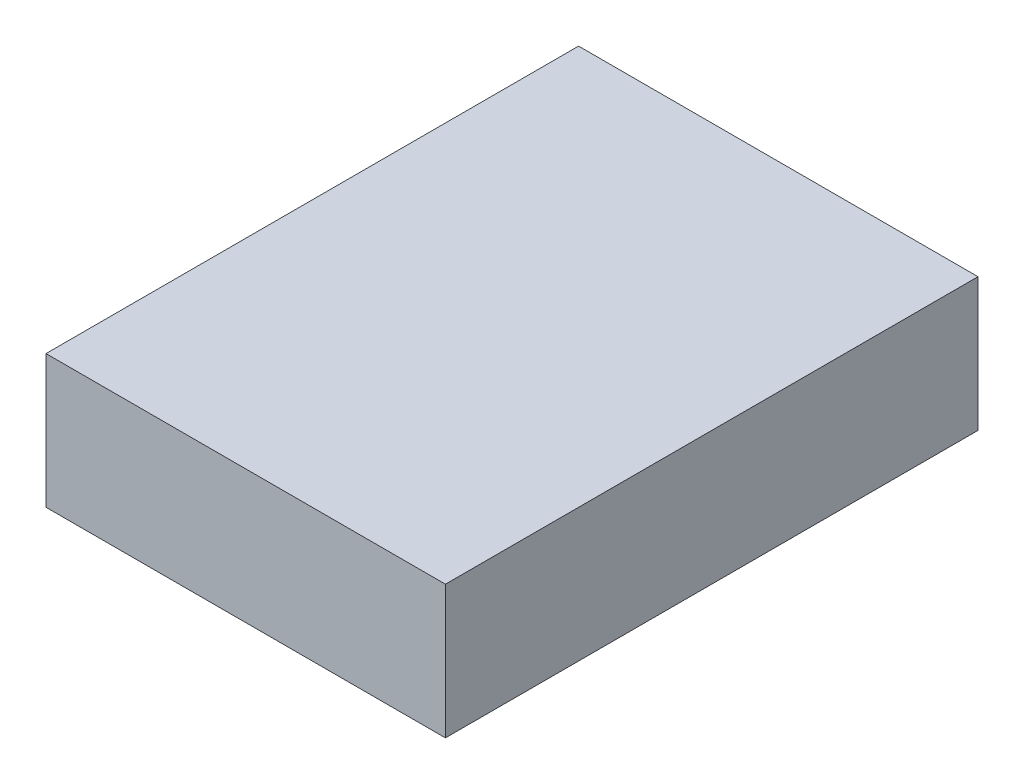
SolidWorks part; units mm, degrees
ref_plane "Front" through (0, 0, 0) normal (0, 0, 1) x (1, 0, 0)
ref_plane "Top" through (0, 0, 0) normal (0, 1, 0) x (1, 0, 0)
ref_plane "Right" through (0, 0, 0) normal (1, 0, 0) x (0, 0, -1)
sketch "Esboço1" plane through (0, 0, 0) normal (0, 1, 0) x (1, 0, 0)
  line L1 (-106.2315, 89.2738) -> (-97.2315, 89.2738)
  line L2 (-106.2315, 89.2738) -> (-106.2315, 77.2738)
  line L3 (-106.2315, 77.2738) -> (-97.2315, 77.2738)
  line L4 (-97.2315, 89.2738) -> (-97.2315, 77.2738)
  line L5 (-106.2315, 89.2738) -> (-97.2315, 77.2738) construction
  line L6 (-106.2315, 77.2738) -> (-97.2315, 89.2738) construction
  point P0 (-101.7315, 83.2738)
  dimension "D1" = 12
  dimension "D2" = 9
extrude "Ressalto-extrusão1" add sketch "Esboço1" along normal blind 3
